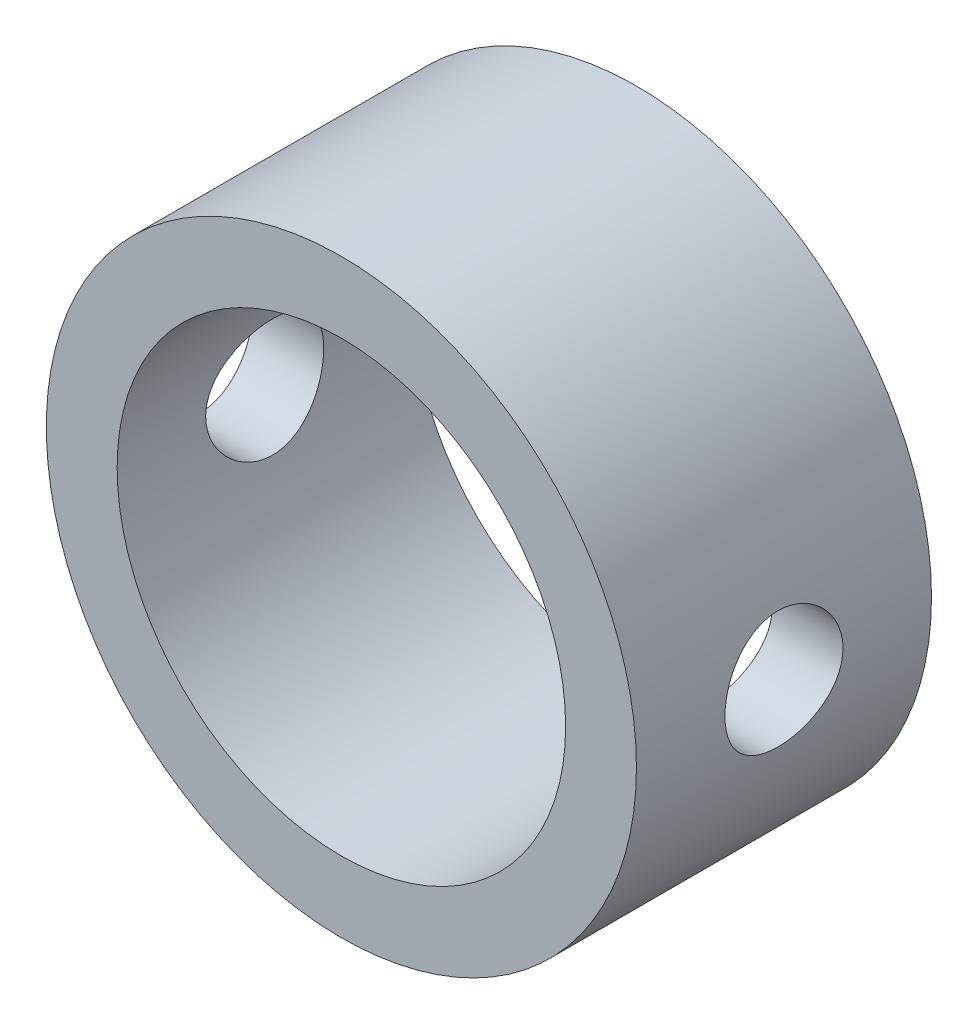
SolidWorks part; units mm, degrees
material "Gerais  - 6061-T6"
ref_plane "Plano frontal" through (0, 0, 0) normal (0, 0, 1) x (1, 0, 0)
ref_plane "Plano superior" through (0, 0, 0) normal (0, 1, 0) x (1, 0, 0)
ref_plane "Plano direito" through (0, 0, 0) normal (1, 0, 0) x (0, 0, -1)
sketch "Esboço1" plane through (0, 0, 0) normal (0, 0, 1) x (1, 0, 0)
  circle A0 centre (0, 0) radius 10
  circle A1 centre (0, 0) radius 7.6
  dimension "D1" = 20
  dimension "D2" = 15.2
extrude "Ressalto-extrusão1" add sketch "Esboço1" along normal blind 10
sketch "Esboço2" plane through (0, 0, 0) normal (1, 0, 0) x (0, 0, -1)
  line L0 (0, 10) -> (-10, 10) construction
  circle A0 centre (-5, 0) radius 2
  point P2 (-5, 10)
  dimension "D1" = 4
extrude "Corte-extrusão1" cut sketch "Esboço2" against normal through all both and the other way through all
